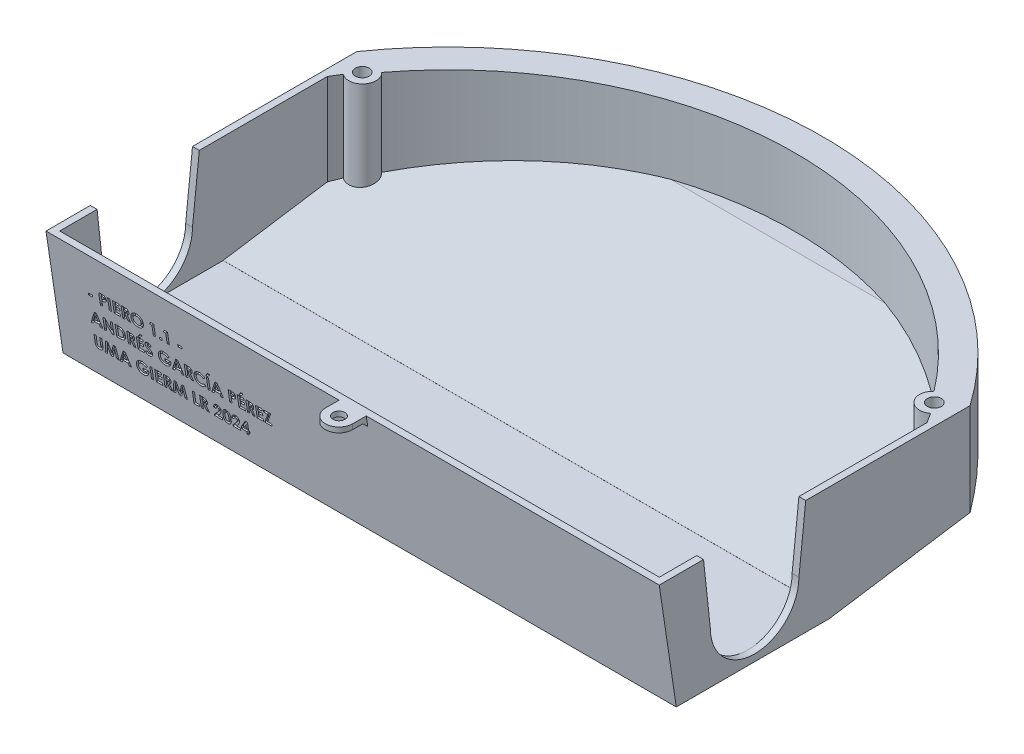
SolidWorks part; units mm, degrees
ref_plane "Alzado" through (0, 0, 0) normal (0, 0, 1) x (1, 0, 0)
ref_plane "Planta" through (0, 0, 0) normal (0, 1, 0) x (1, 0, 0)
ref_plane "Vista lateral" through (0, 0, 0) normal (1, 0, 0) x (0, 0, -1)
sketch "Croquis1" plane through (0, 0, 0) normal (0, 1, 0) x (1, 0, 0)
  line L0 (-110, 0) -> (110, 0) construction
  line L1 (-21.5, -21.5) -> (21.5, -21.5) construction
  line L2 (-21.5, -21.5) -> (-21.5, 21.5) construction
  line L3 (-21.5, 21.5) -> (21.5, 21.5) construction
  line L4 (21.5, -21.5) -> (21.5, 21.5) construction
  line L5 (-21.5, -21.5) -> (21.5, 21.5) construction
  line L6 (-21.5, 21.5) -> (21.5, -21.5) construction
  line L7 (0, 110) -> (0, -110) construction
  line L8 (-129.72, -35) -> (-90.28, -35) construction
  line L9 (-129.72, -35) -> (-129.72, 35) construction
  line L10 (-129.72, 35) -> (-90.28, 35) construction
  line L11 (-90.28, -35) -> (-90.28, 35) construction
  line L12 (-129.72, -35) -> (-90.28, 35) construction
  line L13 (-129.72, 35) -> (-90.28, -35) construction
  line L18 (28.5, 12.25) -> (28.5, -12.25) construction
  line L20 (-28.5, 12.25) -> (-110, 12.25) construction
  line L21 (-28.5, 12.25) -> (-28.5, -12.25) construction
  line L22 (-28.5, -12.25) -> (-110, -12.25) construction
  line L23 (-110, 12.25) -> (-110, -12.25) construction
  line L24 (28.5, 12.25) -> (110, 12.25) construction
  line L25 (28.5, -12.25) -> (110, -12.25) construction
  line L26 (129.72, -35) -> (90.28, -35) construction
  line L27 (90.28, -35) -> (90.28, 35) construction
  line L28 (129.72, 35) -> (90.28, 35) construction
  line L29 (129.72, -35) -> (129.72, 35) construction
  circle A0 centre (0, 0) radius 110 construction
  circle A1 centre (0, -62.5) radius 35 construction
  point P21 (-28.5, 0)
  dimension "D1" = 220
  dimension "D6" = 70
  dimension "D2" = 43
  dimension "D3" = 43
  dimension "D4" = 39.44
  dimension "D5" = 62.5
  dimension "D7" = 70
  dimension "D8" = 81.5
  dimension "D9" = 0
  dimension "D10" = 24.5
sketch "Croquis2" plane through (0, 0, 0) normal (1, 0, 0) x (0, 0, -1)
  line L0 (110, 0) -> (-110, 0) construction
  line L3 (22, -33.5) -> (22, 0) construction
  line L5 (22, -33.5) -> (110, 0)
  line L6 (22, -33.5) -> (-23, -33.5) construction
  line L7 (-28, 0) -> (-23, -33.5) construction
  line L10 (104.7463, 0) -> (110, 0) construction
  line L11 (0, 0) -> (0, -64.3362) construction
  dimension "D1" = 33.5
  dimension "D2" = 22
  dimension "D3" = 45
  dimension "D4" = 28
  dimension "D5" = 110
sketch "Croquis3" plane through (0, 0, 0) normal (1, 0, 0) x (0, 0, -1)
  line L0 (-28, 0) -> (-23, -33.5)
  line L1 (-23, -33.5) -> (22, -33.5)
  line L2 (22, -33.5) -> (22, -31.5)
  line L3 (22, -33.5) -> (22, 0) construction
  line L4 (22, -31.5) -> (-21.2764, -31.5)
  line L5 (-21.2764, -31.5) -> (-25.9778, 0)
  line L6 (110, 0) -> (-110, 0) construction
  line L7 (-28, 0) -> (-25.9778, 0)
  dimension "D1" = 2
  dimension "D2" = 2
extrude "Saliente-Extruir1" add sketch "Croquis3" along normal mid plane 180
sketch "Croquis4" plane through (0, -31.5, 0) normal (0, 1, 0) x (1, 0, 0)
  line L0 (90, -25.9778) -> (-90, -25.9778) construction
  line L1 (-90, 22) -> (-88, 22)
  line L2 (-90, 22) -> (-90, -25.9778)
  line L3 (-90, -25.9778) -> (-88, -25.9778)
  line L4 (-88, 22) -> (-88, -25.9778)
  line L5 (0, -55) -> (0, 55) construction
  line L6 (90, -25.9778) -> (88, -25.9778)
  line L7 (88, 22) -> (88, -25.9778)
  line L8 (90, 22) -> (88, 22)
  line L9 (90, 22) -> (90, -25.9778)
  dimension "D1" = 2
extrude "Saliente-Extruir2" add sketch "Croquis4" along normal through all
sketch "Croquis5" plane through (-90, 0, 0) normal (-1, 0, 0) x (0, 0, 1)
  line L0 (25.9778, -31.5) -> (25.9778, -13.5484)
  line L1 (25.9778, -13.5484) -> (23.2985, -31.5)
  line L2 (23.2985, -31.5) -> (25.9778, -31.5)
  line L4 (-13, -18.5) -> (-15, 0)
  line L5 (-22, 0) -> (28, 0) construction
  line L6 (0, 0) -> (0, -18.5) construction
  line L7 (13, -18.5) -> (15, 0)
  line L8 (-15, 0) -> (15, 0)
  arc A0 (-13, -18.5) -> (13, -18.5) centre (0, -18.5) ccw
  point P7 (0, -31.5)
  dimension "D2" = 13
  dimension "D1" = 31.5
  dimension "D3" = 15
extrude "Cortar-Extruir1" cut sketch "Croquis5" against normal through all
sketch "Croquis8" plane through (0, 0, 0) normal (1, 0, 0) x (0, 0, -1)
  line L0 (110, -20) -> (22, -33.5)
  line L1 (110, -20) -> (110, 0)
  dimension "D1" = 20
sketch "Croquis12" plane through (0, 0, 0) normal (1, 0, 0) x (0, 0, -1)
  line L0 (22, -33.5) -> (110, -20)
  line L2 (96.8104, -20) -> (22, -31.4766)
  line L3 (22, -31.4766) -> (22, -33.5)
  line L4 (110, -20) -> (22, -33.5) construction
  line L5 (110, -20) -> (96.8104, -20)
  dimension "D1" = 2
extrude "Saliente-Extruir4" add sketch "Croquis12" along normal mid plane 180
sketch "Croquis15" plane through (0, 0, 0) normal (0, 1, 0) x (1, 0, 0)
  circle A0 centre (0, 0) radius 110
  circle A1 centre (0, 0) radius 150
  dimension "D1" = 300
extrude "Cortar-Extruir3" cut sketch "Croquis15" against normal through all
sketch "Croquis13" plane through (0, 0, 0) normal (0, 1, 0) x (1, 0, 0)
  line L10 (0, 0) -> (0, 110) construction
  line L11 (90, 22) -> (88, 22)
  line L12 (90, 22) -> (90, 63.2456)
  line L14 (88, 22) -> (88, 52.5571)
  line L15 (-90, 22) -> (-90, 63.2456)
  line L16 (-90, 22) -> (-88, 22)
  line L17 (-88, 22) -> (-88, 52.5571)
  line L18 (-90.1067, 63.0934) -> (0, 0) construction
  arc A0 (90, 63.2456) -> (-90, 63.2456) centre (0, 0) ccw
  arc A2 (-86.1916, 55.473) -> (-88, 52.5571) centre (0, 0) ccw
  arc A3 (81.0549, 61.5947) -> (-81.0549, 61.5947) centre (0, 0) ccw
  arc A4 (-86.1916, 55.473) -> (-81.0549, 61.5947) centre (-83.766, 58.6536) ccw
  arc A5 (86.1916, 55.473) -> (81.0549, 61.5947) centre (83.766, 58.6536) cw
  arc A6 (86.1916, 55.473) -> (88, 52.5571) centre (0, 0) cw
  dimension "D3" = 110
  dimension "D7" = 8
  dimension "D1" = 2
  dimension "D4" = 55
extrude "Saliente-Extruir5" add sketch "Croquis13" against normal up to next
sketch "Croquis16" plane through (0, 0, 0) normal (0, 1, 0) x (1, 0, 0)
  line L0 (90, -28) -> (-90, -28) construction
  line L1 (-4, -28) -> (4, -28)
  line L2 (-4, -28) -> (-4, -32)
  line L4 (4, -28) -> (4, -32)
  line L5 (0, 0) -> (0, -32) construction
  circle A0 centre (0, -32) radius 1.75
  arc A1 (-4, -32) -> (4, -32) centre (0, -32) ccw
  dimension "D3" = 3.5
  dimension "D1" = 8
  dimension "D4" = 4
extrude "Saliente-Extruir6" add sketch "Croquis16" against normal blind 1.5 separate body
sketch "Croquis17" plane through (0, 0, 0) normal (0, 1, 0) x (1, 0, 0)
  line L0 (-83.9631, 58.7916) -> (0, 0) construction
  line L1 (0, 0) -> (0, 62.2458) construction
  circle A0 centre (0, 0) radius 102.5 construction
  circle A1 centre (-83.9631, 58.7916) radius 2.05
  circle A2 centre (83.9631, 58.7916) radius 2.05
  dimension "D1" = 205
  dimension "D2" = 4.1
  dimension "D3" = 55
extrude "Cortar-Extruir4" cut sketch "Croquis17" against normal blind 5.2
sketch "Croquis18" plane through (0, 0, 0) normal (1, 0, 0) x (0, 0, -1)
  line L0 (-28, -1.5) -> (-28, 0)
  line L1 (-28, 0) -> (-27.5614, -2.9386)
  line L2 (-28, 0) -> (-23, -33.5) construction
  line L3 (-27.5614, -2.9386) -> (-29, -1.5)
  line L4 (-32, -1.5) -> (-28, -1.5) construction
  line L5 (-29, -1.5) -> (-28, -1.5)
  line L6 (-28, -1.5) -> (-27.7761, -1.5) construction
  dimension "D1" = 45
  dimension "D2" = 1
extrude "Saliente-Extruir7" add sketch "Croquis18" along normal mid plane 8
sketch "Croquis19" plane through (0, -4.088, 27.3898) normal (0, -0.1476, 0.989) x (1, 0, 0)
  text T0 "<b>- PIERO 1.1 -</b>\r\n<b>ANDRÉS GARCÍA PÉREZ</b>\r\n<b>UMA GIERM LR 2024</b>"
extrude "Cortar-Extruir5" cut sketch "Croquis19" against normal blind 0.6
